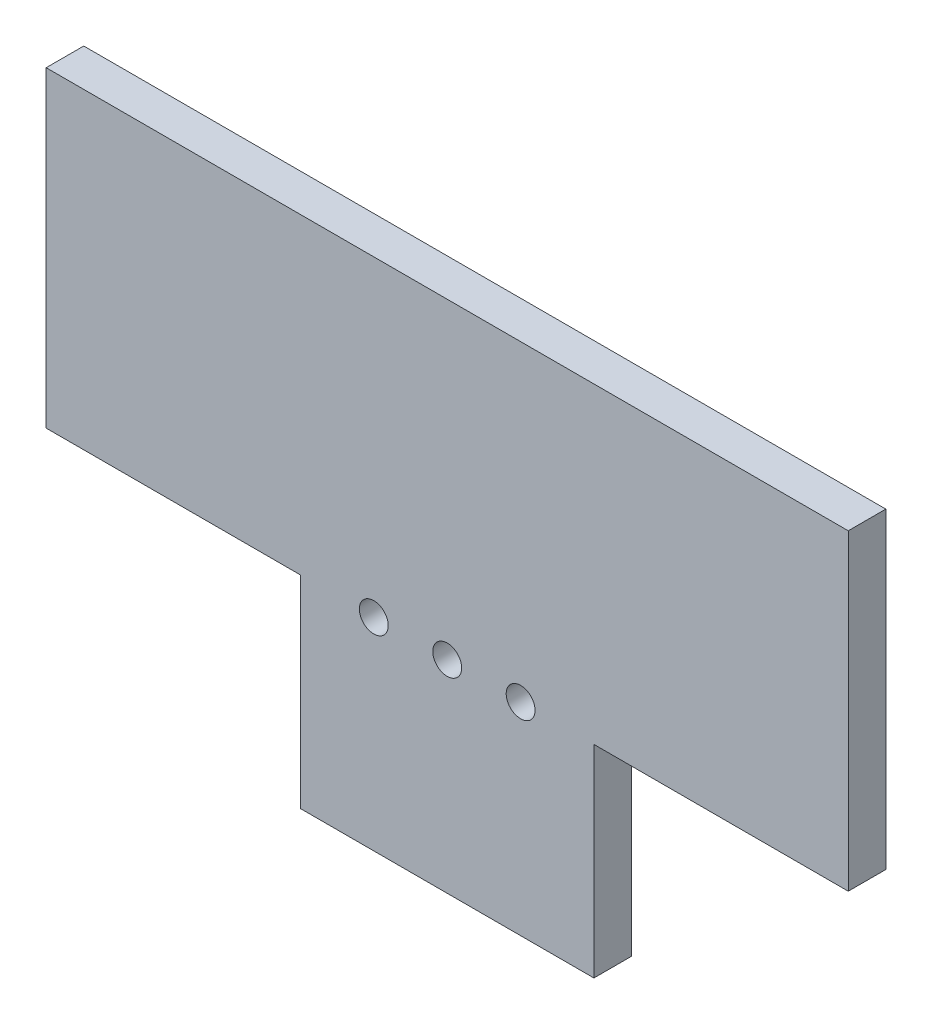
SolidWorks part; units mm, degrees
ref_plane "Front" through (0, 0, 0) normal (0, 0, 1) x (1, 0, 0)
ref_plane "Top" through (0, 0, 0) normal (0, 1, 0) x (1, 0, 0)
ref_plane "Right" through (0, 0, 0) normal (1, 0, 0) x (0, 0, -1)
sketch "Sketch1" plane through (0, 0, 0) normal (0, 0, 1) x (1, 0, 0)
  line L0 (5.075, -12.4) -> (5.075, -5.4)
  line L1 (5.075, -5.4) -> (13.875, -5.4)
  line L2 (13.875, -5.4) -> (13.875, 5.4)
  line L3 (13.875, 5.4) -> (-13.875, 5.4)
  line L4 (-13.875, 5.4) -> (-13.875, -5.4)
  line L5 (-13.875, -5.4) -> (-5.075, -5.4)
  line L6 (-5.075, -5.4) -> (-5.075, -12.4)
  line L7 (-5.075, -12.4) -> (5.075, -12.4)
  line L8 (0, -12.4) -> (0, 5.4) construction
  point P2 (0, 0)
  dimension "D1" = 27.75
  dimension "D2" = 10.15
  dimension "D3" = 5.4
  dimension "D4" = 10.8
  dimension "D5" = 17.8
extrude "Extrude1" add sketch "Sketch1" along normal mid plane 1.3
sketch "Sketch3" plane through (0, 0, 0.65) normal (0, 0, 1) x (1, 0, 0)
  circle A0 centre (2.54, -5.4) radius 0.5
  point P2 (0, 0)
  dimension "D1" = 1
  dimension "D2" = 2.54
  dimension "D3" = 5.4
extrude "Cut-Extrude1" cut sketch "Sketch3" against normal up to next
pattern_linear "LPattern1" count 3 spacing 2.54 along (-1, 0, 0) of "Cut-Extrude1"
